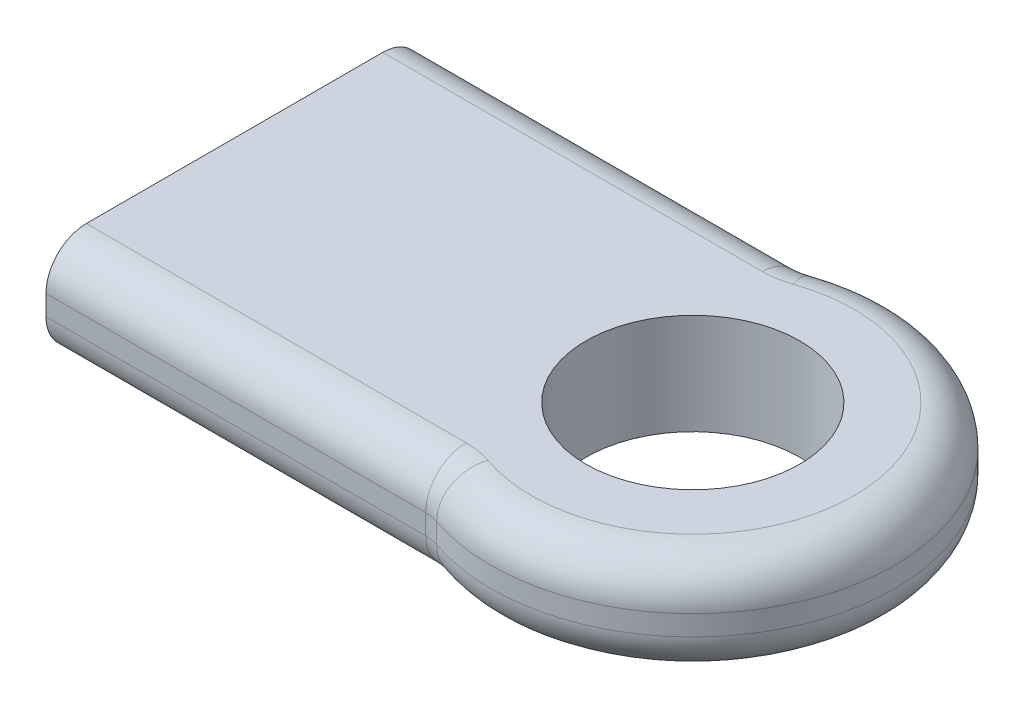
SolidWorks part; units mm, degrees
ref_plane "Alzado" through (0, 0, 0) normal (0, 0, 1) x (1, 0, 0)
ref_plane "Planta" through (0, 0, 0) normal (0, 1, 0) x (1, 0, 0)
ref_plane "Vista lateral" through (0, 0, 0) normal (1, 0, 0) x (0, 0, -1)
sketch "Croquis1" plane through (0, 0, 0) normal (0, 1, 0) x (1, 0, 0)
  line L0 (-1000, 0) -> (49000, 0) construction
  line L1 (-22.7251, 6.35) -> (-7.7251, 6.35) construction
  line L2 (-22.7251, -6.35) -> (-7.7251, -6.35) construction
  line L3 (-22.7251, 9.35) -> (-3.5465, 9.35)
  line L4 (-29.2705, 9.35) -> (-7.7251, 9.35) construction
  line L5 (-22.7251, -9.35) -> (-3.5465, -9.35)
  line L6 (-29.2705, 6.35) -> (-7.7251, 6.35) construction
  line L7 (-22.7251, 9.35) -> (-22.7251, -9.35)
  circle A0 centre (0, 0) radius 5.3
  arc A1 (-3.5465, -9.35) -> (-3.5465, 9.35) centre (0, 0) ccw
  point P3 (0, 0)
  point P8 (-8.2044, 6.35)
  dimension "D1" = 10.6
  dimension "D2" = 20
  dimension "D3" = 12.7
  dimension "D5" = 15
  dimension "D4" = 3
extrude "Saliente-Extruir1" add sketch "Croquis1" along normal mid plane 5
sketch "Croquis2" plane through (-22.7251, 0, 0) normal (-1, 0, 0) x (0, 0, 1)
  line L0 (-6.55, 1) -> (6.55, 1)
  line L1 (-6.35, 0.8) -> (6.35, 0.8) construction
  line L2 (-6.35, 0.8) -> (-6.35, -0.8) construction
  line L3 (-6.35, -0.8) -> (6.35, -0.8) construction
  line L4 (6.35, 0.8) -> (6.35, -0.8) construction
  line L5 (-6.35, 0.8) -> (6.35, -0.8) construction
  line L6 (-6.35, -0.8) -> (6.35, 0.8) construction
  line L7 (6.55, 1) -> (6.55, -1)
  line L8 (-6.55, -1) -> (6.55, -1)
  line L9 (-6.55, 1) -> (-6.55, -1)
  point P0 (0, 0)
  dimension "D1" = 12.7
  dimension "D2" = 1.6
  dimension "D3" = 0.2
extrude "Cortar-Extruir1" cut sketch "Croquis2" against normal blind 15
fillet "Redondeo1" radius 2 8 edges at (-13.1358, 2.5, 9.35) (-13.1358, -2.5, 9.35) (-3.5465, 0, 9.35) (10, 2.5, 0) (10, -2.5, 0) (-3.5465, 0, -9.35) (-13.1358, 2.5, -9.35) (-13.1358, -2.5, -9.35)
